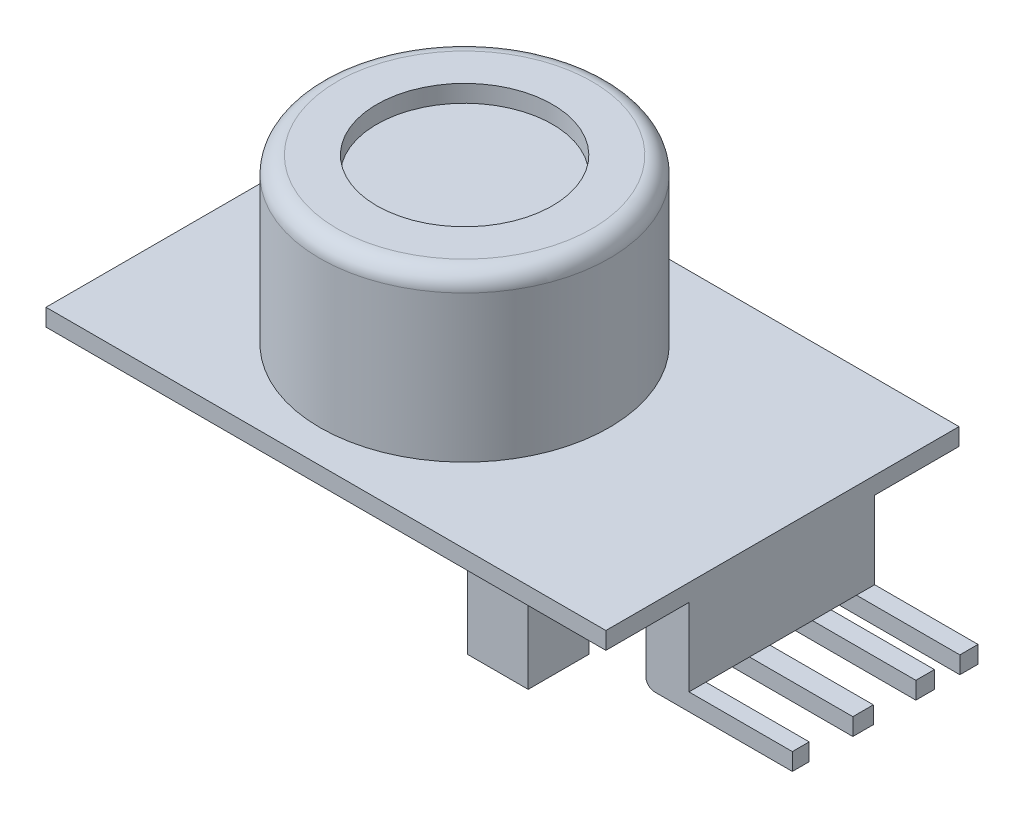
SolidWorks part; units mm, degrees
ref_plane "Alzado" through (0, 0, 0) normal (0, 0, 1) x (1, 0, 0)
ref_plane "Planta" through (0, 0, 0) normal (0, 1, 0) x (1, 0, 0)
ref_plane "Vista lateral" through (0, 0, 0) normal (1, 0, 0) x (0, 0, -1)
sketch "Croquis1" plane through (0, 0, 0) normal (0, 1, 0) x (1, 0, 0)
  line L1 (0, 0) -> (32.5, 0)
  line L2 (0, 0) -> (0, 20.5)
  line L3 (0, 20.5) -> (32.5, 20.5)
  line L4 (32.5, 0) -> (32.5, 20.5)
extrude "Saliente-Extruir1" add sketch "Croquis1" along normal blind 1
sketch "Croquis2" plane through (0, 1, 0) normal (0, 1, 0) x (1, 0, 0)
  line L0 (32.5, 20.5) -> (0, 20.5) construction
  line L1 (0, 20.5) -> (0, 0) construction
  circle A0 centre (14, 10.3) radius 8.4
  point P7 (12.7013, 10.7074)
  dimension "D1" = 16.8
  dimension "D2" = 10.2
  dimension "D3" = 14
extrude "Saliente-Extruir2" add sketch "Croquis2" along normal blind 9.5
sketch "Croquis3" plane through (0, 0, 0) normal (0, -1, 0) x (1, 0, 0)
  line L0 (32.5, 0) -> (32.5, -20.5) construction
  line L1 (32.5, -4.8248) -> (30, -4.8248)
  line L2 (32.5, -4.8248) -> (32.5, -15.6016)
  line L3 (32.5, -15.6016) -> (30, -15.6016)
  line L4 (30, -4.8248) -> (30, -15.6016)
  dimension "D1" = 2.5
extrude "Saliente-Extruir3" add sketch "Croquis3" along normal blind 5.5
sketch "Croquis4" plane through (32.5, 0, 0) normal (1, 0, 0) x (0, 0, -1)
  line L0 (15.6016, -5.5) -> (15.6016, 0) construction
  line L1 (4.8248, -5.5) -> (15.6016, -5.5)
  line L2 (4.8248, -5.5) -> (4.8248, -4.5)
  line L3 (4.8248, -4.5) -> (15.6016, -4.5)
  line L4 (15.6016, -5.5) -> (15.6016, -4.5)
extrude "Saliente-Extruir4" add sketch "Croquis4" along normal blind 6
sketch "Croquis5" plane through (0, 0, 0) normal (0, -1, 0) x (1, 0, 0)
  line L1 (23.6702, -0.7835) -> (27.2063, -0.7835)
  line L2 (23.6702, -0.7835) -> (23.6702, -4.3196)
  line L3 (23.6702, -4.3196) -> (27.2063, -4.3196)
  line L4 (27.2063, -0.7835) -> (27.2063, -4.3196)
extrude "Saliente-Extruir5" add sketch "Croquis5" along normal blind 5
sketch "Croquis7" plane through (0, 10.5, 0) normal (0, 1, 0) x (1, 0, 0)
  circle A0 centre (14, 10.3) radius 5.1
  point P0 (14, 10.3)
extrude "Cortar-Extruir1" cut sketch "Croquis7" against normal blind 1
fillet "Redondeo1" radius 1 1 edges at (14, 10.5, -1.9)
sketch "Croquis8" plane through (38.5, 0, 0) normal (1, 0, 0) x (0, 0, -1)
  line L0 (15.6016, -4.5) -> (4.8248, -4.5) construction
  line L2 (4.8248, -5.5) -> (4.8248, -4.5)
  line L4 (5.8034, -5.5) -> (5.8034, -4.5)
  line L5 (15.6016, -4.5) -> (4.8248, -4.5) construction
  line L9 (14.5484, -5.5) -> (14.5484, -4.5)
  line L11 (13.0725, -4.5) -> (13.0725, -5.5)
  line L13 (11.9932, -4.5) -> (11.9932, -5.5)
  line L14 (4.8248, -5.5) -> (15.6016, -5.5) construction
  line L15 (5.8034, -4.5) -> (8.3365, -4.5)
  line L17 (8.3365, -4.5) -> (8.3365, -5.5)
  line L19 (9.526, -4.5) -> (9.526, -5.5)
  line L20 (5.8034, -5.5) -> (8.3365, -5.5)
  line L21 (9.526, -5.5) -> (11.9932, -5.5)
  line L22 (9.526, -5.5) -> (11.9932, -5.5)
  line L23 (4.8248, -4.5) -> (4.8248, -5.5)
  line L24 (4.8248, -5.5) -> (15.6016, -5.5)
  line L25 (15.6016, -5.5) -> (15.6016, -4.5)
  line L26 (15.6016, -4.5) -> (4.8248, -4.5)
  line L27 (4.8248, -4.5) -> (4.8248, -5.5)
  line L28 (5.8034, -5.5) -> (8.3365, -5.5)
  line L30 (14.5484, -4.5) -> (13.0725, -4.5)
  line L31 (9.526, -4.5) -> (11.9932, -4.5)
  line L32 (8.3365, -4.5) -> (5.8034, -4.5)
  line L33 (11.9932, -4.5) -> (9.526, -4.5)
  line L34 (13.0725, -4.5) -> (14.5484, -4.5)
  line L35 (13.0725, -5.5) -> (14.5484, -5.5)
  line L36 (13.0725, -5.5) -> (14.5484, -5.5)
  line M22 (4.8248, -5.5) -> (15.6016, -5.5)
  line M24 (15.6016, -4.5) -> (4.8248, -4.5)
  dimension "D1" = 0
extrude "Cortar-Extruir2" cut sketch "Croquis8" against normal blind 12 contours L17 L4 M24 M22 | L19 L13 M24 M22 | L11 L9 M24 M22
fillet "Redondeo2" radius 0.5 4 edges at (30, -5.5, -5.3141) (30, -5.5, -8.9313) (30, -5.5, -12.5328) (30, -5.5, -15.075)
